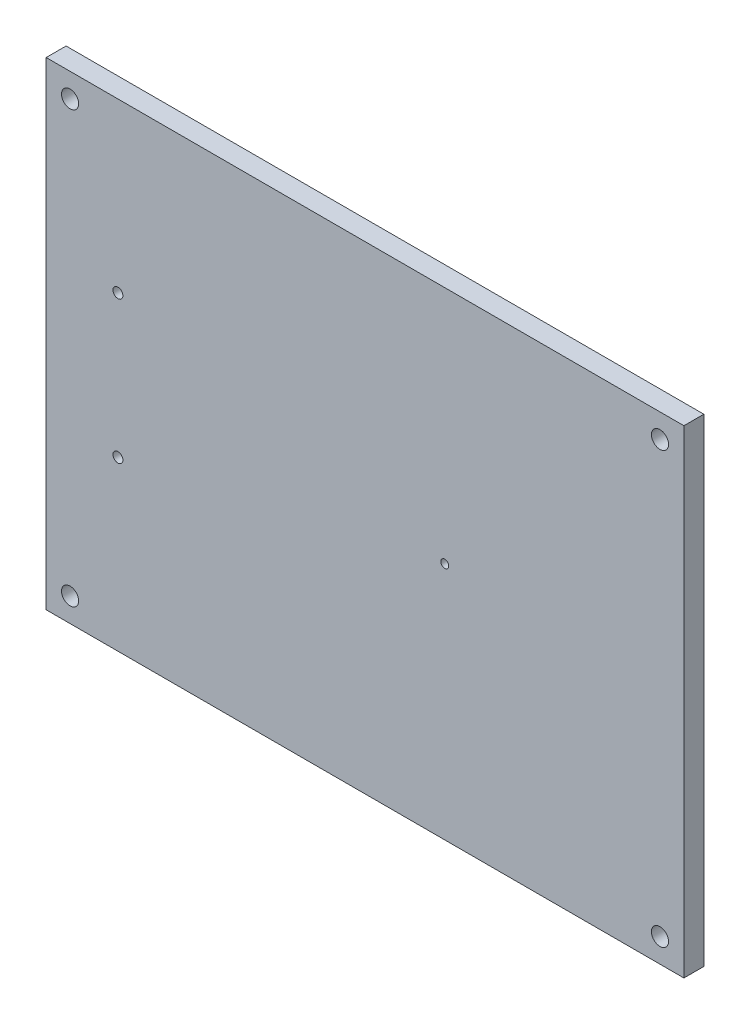
SolidWorks part; units mm, degrees
material "Acrylic (Medium-high impact)"
ref_plane "Front Plane" through (0, 0, 0) normal (0, 0, 1) x (1, 0, 0)
ref_plane "Top Plane" through (0, 0, 0) normal (0, 1, 0) x (1, 0, 0)
ref_plane "Right Plane" through (0, 0, 0) normal (1, 0, 0) x (0, 0, -1)
sketch "Sketch1" plane through (0, 0, 0) normal (0, 0, 1) x (1, 0, 0)
  line L0 (-10, -55) -> (150, -55)
  line L1 (150, -55) -> (150, 65)
  line L2 (150, 65) -> (-10, 65)
  line L3 (-10, 65) -> (-10, -55)
  circle A0 centre (90, 5) radius 1
  circle A1 centre (8, -12.87) radius 1.25
  circle A2 centre (8, 22.87) radius 1.25
  circle A3 centre (-4, -49) radius 2.15
  circle A4 centre (144, -49) radius 2.15
  circle A5 centre (144, 59) radius 2.15
  circle A6 centre (-4, 59) radius 2.15
  dimension "D3" = 2
  dimension "D5" = 2.5
  dimension "D8" = 4.3
  dimension "D1" = 160
  dimension "D2" = 120
  dimension "D4" = 100
  dimension "D6" = 18
  dimension "D7" = 77.87
  dimension "D9" = 6
  dimension "D10" = 6
extrude "Boss-Extrude1" add sketch "Sketch1" along normal blind 5
